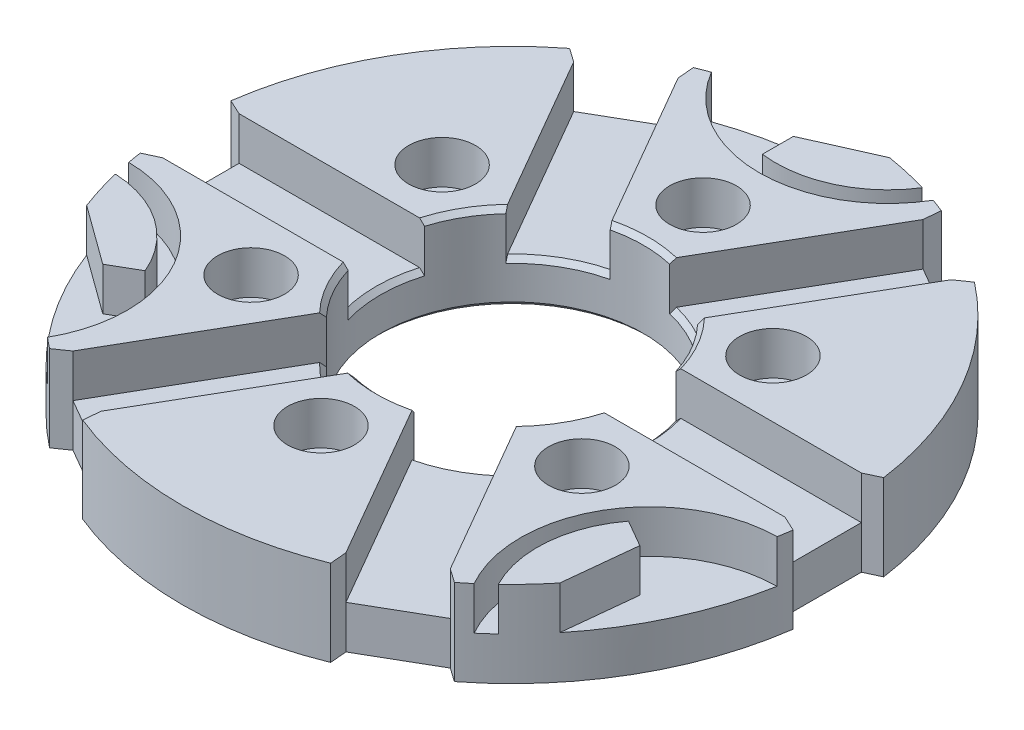
SolidWorks part; units mm, degrees
ref_plane "Front Plane" through (0, 0, 0) normal (0, 0, 1) x (1, 0, 0)
ref_plane "Top Plane" through (0, 0, 0) normal (0, 1, 0) x (1, 0, 0)
ref_plane "Right Plane" through (0, 0, 0) normal (1, 0, 0) x (0, 0, -1)
sketch "Sketch1" plane through (0, 0, 0) normal (0, 1, 0) x (1, 0, 0)
  circle A0 centre (0, 0) radius 69
  dimension "D1" = 138
extrude "Boss-Extrude1" add sketch "Sketch1" along normal blind 18
sketch "Sketch2" plane through (0, 18, 0) normal (0, 1, 0) x (1, 0, 0)
  circle A0 centre (0, 0) radius 27.5
  dimension "D1" = 55
extrude "Cut-Extrude1" cut sketch "Sketch2" against normal through all
sketch "Sketch3" plane through (0, 18, 0) normal (0, 1, 0) x (1, 0, 0)
  line L0 (0, -69) -> (0, 69) construction
  line L1 (-69, 0) -> (69, 0) construction
  line L2 (-39.5062, 52.4268) -> (-20.0835, 18.7857)
  line L3 (-6.2271, 26.7857) -> (-25.6498, 60.4268)
  line L5 (-34.5, 59.7558) -> (0, 0) construction
  line L6 (-24, 41.5692) -> (-25.6498, 60.4268) construction
  line L7 (-24, 41.5692) -> (-39.5062, 52.4268) construction
  line L8 (-39.5062, 52.4268) -> (-42.3882, 54.4448)
  line L9 (-25.6498, 60.4268) -> (-25.9565, 63.9317)
  arc A1 (-6.2271, 26.7857) -> (-20.0835, 18.7857) centre (0, 0) ccw
  circle A2 centre (0, 0) radius 69 construction
  circle A3 centre (0, 0) radius 27.5 construction
  arc A7 (-25.9565, 63.9317) -> (-42.3882, 54.4448) centre (0, 0) ccw
  arc A8 (0, 48) -> (-48, 0) centre (0, 0) ccw construction
  point P14 (-26.2997, 61.1526)
  point P18 (0, 0)
  dimension "D1" = 48
  dimension "D2" = 30
  dimension "D3" = 8
  dimension "D4" = 8
  dimension "D5" = 50
extrude "Cut-Extrude2" cut sketch "Sketch3" against normal blind 9
sketch "Sketch4" plane through (0, 9, 0) normal (0, 1, 0) x (1, 0, 0)
  line L0 (-39.5062, 52.4268) -> (-25.6498, 60.4268)
  line L1 (-25.6498, 60.4268) -> (-25.9565, 63.9317)
  line L2 (-39.5062, 52.4268) -> (-42.3882, 54.4448)
  arc A0 (-25.9565, 63.9317) -> (-42.3882, 54.4448) centre (0, 0) ccw
extrude "Cut-Extrude3" cut sketch "Sketch4" against normal blind 9
pattern_circular "CirPattern1" count 6 over 360 about axis through (0, 0, 0) along (0, 1, 0) of "Cut-Extrude2", "Cut-Extrude3"
sketch "Sketch5" plane through (0, 18, 0) normal (0, 1, 0) x (1, 0, 0)
  line L0 (0, 0) -> (-59.7558, -34.5) construction
  line L1 (-59.7558, -34.5) -> (-76.6432, -44.25) construction
  line L2 (0, 0) -> (-32.578, 56.4268) construction
  line L3 (-39.5062, 52.4268) -> (-25.6498, 60.4268) construction
  line L4 (-52.1307, -33.5618) -> (-46.5144, -30.3192)
  line L5 (-52.1307, -33.5618) -> (-64.4659, -24.5997)
  arc A0 (-68.3447, -9.4869) -> (-42.3882, -54.4448) centre (0, 0) ccw construction
  circle A1 centre (-68.1995, -39.375) radius 27
  arc A2 (-46.5144, -30.3192) -> (-67.1434, -15.8987) centre (-68.1995, -39.375) ccw
  arc A3 (-59.4613, -17.56) -> (-44.9381, -42.715) centre (0, 0) ccw construction
  arc A4 (-67.1434, -15.8987) -> (-64.4659, -24.5997) centre (0, 0) ccw
  dimension "D2" = 54
  dimension "D3" = 47
  dimension "D6" = 62
  dimension "D1" = 78.75
  dimension "D4" = 66
  dimension "D5" = 3
extrude "Cut-Extrude4" cut sketch "Sketch5" against normal blind 9
pattern_circular "CirPattern2" count 3 over 360 about axis through (0, 0, 0) along (0, 1, 0) of "Cut-Extrude4"
ref_plane "Plane1" through (0, 18, 0) normal (0, 1, 0) x (1, 0, 0)
hole_wizard "CBORE for M5 Hex Head Bolt1" positions "3DSketch1" profile "Sketch7" counterbore size "M5" standard "ANSI Metric" end condition through all
sketch3d "3DSketch1"
  line L3 (0, 0, 0) -> (0, 9, 0) construction
  line L7 (0, 18, 0) -> (0, 18, -51.75) construction
  circle A3 centre (0, 18, 0) radius 40 construction
  arc A4 (-23.2217, 18, -64.975) -> (23.2217, 18, -64.975) centre (0, 18, -78.75) ccw construction
  point P0 (0, 18, -40)
  point P30 (0, 58, 0)
  point P49 (0, 45, -78.75)
  point P51 (0, 0, 0)
  dimension "D1" = 80
sketch "Sketch7" plane through (0, 18, -40) normal (1, 0, 0) x (0, 0, 1)
  line L0 (0, 0) -> (0, 18)
  line L1 (0, 18) -> (4.5, 18)
  line L3 (4.5, 18) -> (4.5, 9)
  line L4 (4.5, 9) -> (7, 9)
  line L5 (7, 9) -> (7, 0)
  line L7 (7, 0) -> (0, 0)
  line L11 (0, -6.35) -> (0, 107.95) construction
  dimension "Thru Hole Dia." = 9
  dimension "Thru Hole Depth" = 18
  dimension "C'Bore Dia." = 14
  dimension "C'Bore Depth" = 9
pattern_circular "CirPattern3" count 6 over 360 about axis through (0, 0, 0) along (0, 1, 0) of "CBORE for M5 Hex Head Bolt1"
chamfer "Chamfer1" distance 1 angle 45 13 edges at (0, 0, 27.5) (23.8157, 18, -13.75) (13.75, 9, -23.8157) (0, 18, -27.5) (27.5, 9, 0) (23.8157, 18, 13.75) (13.75, 9, 23.8157) (0, 18, 27.5) (-13.75, 9, 23.8157) (-23.8157, 18, 13.75) (-27.5, 9, 0) (-23.8157, 18, -13.75) (-13.75, 9, -23.8157)
